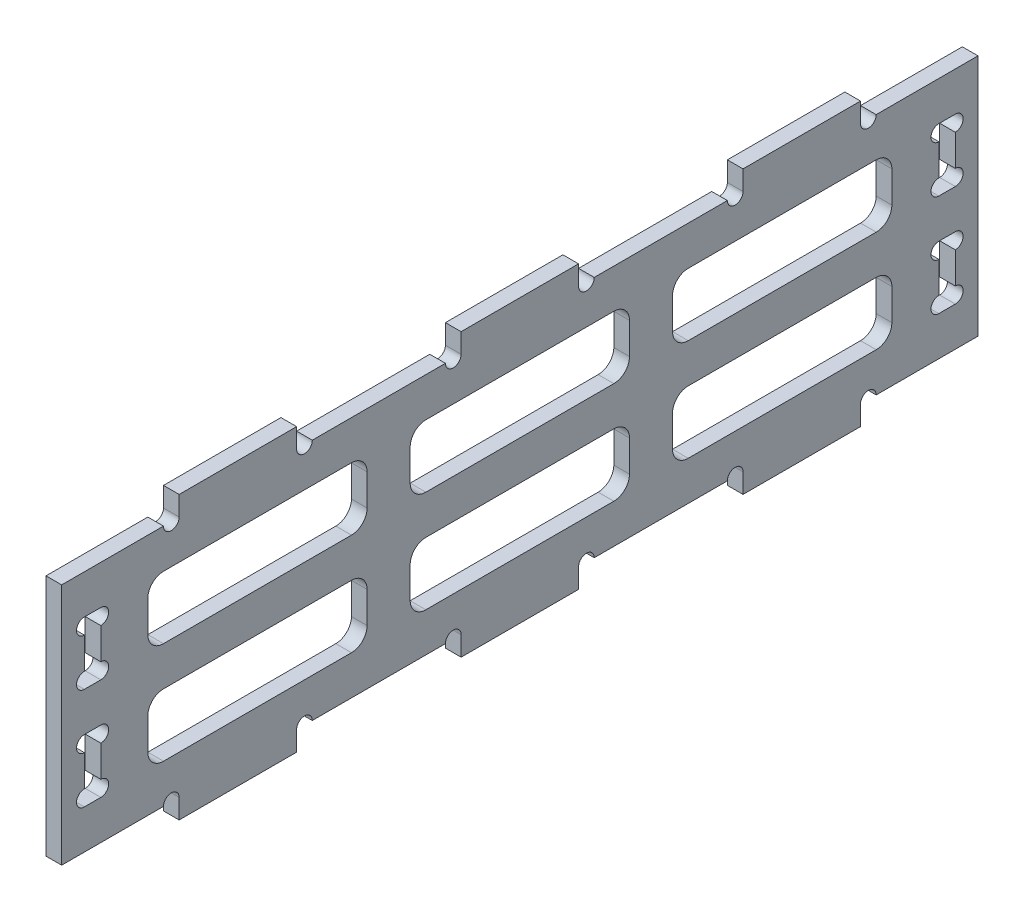
SolidWorks part; units mm, degrees
ref_plane "前视基准面" through (0, 0, 0) normal (0, 0, 1) x (1, 0, 0)
ref_plane "上视基准面" through (0, 0, 0) normal (0, 1, 0) x (1, 0, 0)
ref_plane "右视基准面" through (0, 0, 0) normal (1, 0, 0) x (0, 0, -1)
sketch "草图1" plane through (0, 0, 0) normal (1, 0, 0) x (0, 0, -1)
  line L1 (0, 0) -> (107, 0)
  line L2 (0, 0) -> (0, 31)
  line L3 (0, 31) -> (107, 31)
  line L4 (107, 0) -> (107, 31)
  dimension "D1" = 31
  dimension "D2" = 107
extrude "凸台-拉伸1" add sketch "草图1" along normal blind 2
sketch "草图2" plane through (2, 0, 0) normal (1, 0, 0) x (0, 0, -1)
  line L0 (0, 31) -> (-5, 31)
  line L1 (-5, 31) -> (-5, 0)
  line L2 (-5, 0) -> (0, 0)
  line L4 (0, 31) -> (0, 26)
  line L5 (0, 31) -> (0, 0) construction
  line L6 (0, 26) -> (-2.1, 26)
  line L7 (-2.1, 26) -> (-2.1, 18)
  line L8 (-2.1, 18) -> (0, 18)
  line L9 (0, 18) -> (0, 13)
  line L10 (0, 13) -> (-2.1, 13)
  line L11 (-2.1, 13) -> (-2.1, 5)
  line L12 (-2.1, 5) -> (0, 5)
  line L13 (0, 0) -> (0, 5)
  line L14 (53.5, 31) -> (53.5, 0) construction
  line L15 (107, 31) -> (0, 31) construction
  line L16 (0, 0) -> (107, 0) construction
  line L17 (107, 0) -> (107, 5)
  line L18 (109.1, 5) -> (107, 5)
  line L19 (109.1, 13) -> (109.1, 5)
  line L20 (107, 13) -> (109.1, 13)
  line L21 (107, 18) -> (107, 13)
  line L22 (109.1, 18) -> (107, 18)
  line L23 (109.1, 26) -> (109.1, 18)
  line L24 (107, 26) -> (109.1, 26)
  line L25 (107, 31) -> (107, 26)
  line L26 (112, 0) -> (107, 0)
  line L27 (112, 31) -> (112, 0)
  line L28 (107, 31) -> (112, 31)
  dimension "D1" = 5
  dimension "D2" = 8
  dimension "D3" = 5
  dimension "D4" = 8
  dimension "D5" = 2.1
  dimension "D6" = 5
extrude "凸台-拉伸2" add sketch "草图2" against normal up to surface (2 mm away) up to face at (0, 15.5, -53.5)
sketch "草图3" plane through (2, 0, 0) normal (1, 0, 0) x (0, 0, -1)
  line L0 (-2.1, 24) -> (-2.1, 26)
  line L1 (-2.1, 18) -> (-2.1, 26) construction
  line L2 (-1.05, 26) -> (-1.05, 18) construction
  line L3 (-2.1, 26) -> (0, 26) construction
  line L4 (0, 18) -> (-2.1, 18) construction
  line L5 (-2.1, 22) -> (0, 22) construction
  line L6 (0, 26) -> (0, 18) construction
  line L7 (0, 24) -> (0, 26)
  line L8 (0, 20) -> (0, 18)
  line L9 (-2.1, 20) -> (-2.1, 18)
  line L10 (-1.05, 18) -> (-1.05, 13) construction
  line L11 (-2.1, 13) -> (0, 13) construction
  line L12 (-1.05, 15.5) -> (0, 15.5) construction
  line L13 (-2.1, 9) -> (0, 9) construction
  line L14 (-1.05, 5) -> (-1.05, 13) construction
  line L15 (-2.1, 11) -> (-2.1, 13)
  line L16 (0, 11) -> (0, 13)
  line L17 (0, 7) -> (0, 5)
  line L18 (-2.1, 7) -> (-2.1, 5)
  line L19 (53.5, 31) -> (53.5, 0) construction
  line L20 (112, 31) -> (-5, 31) construction
  line L21 (-5, 0) -> (112, 0) construction
  line L22 (108.05, 5) -> (108.05, 13) construction
  line L23 (109.1, 9) -> (107, 9) construction
  line L24 (108.05, 15.5) -> (107, 15.5) construction
  line L25 (108.05, 18) -> (108.05, 13) construction
  line L26 (109.1, 22) -> (107, 22) construction
  line L27 (108.05, 26) -> (108.05, 18) construction
  line L28 (109.1, 7) -> (109.1, 5)
  line L29 (107, 7) -> (107, 5)
  line L30 (107, 11) -> (107, 13)
  line L31 (109.1, 11) -> (109.1, 13)
  line L32 (109.1, 20) -> (109.1, 18)
  line L33 (107, 20) -> (107, 18)
  line L34 (107, 24) -> (107, 26)
  line L35 (109.1, 24) -> (109.1, 26)
  line L36 (109.1, 26) -> (109.1, 18) construction
  arc A0 (-2.1, 26) -> (-2.1, 24) centre (-2.1, 25) ccw
  arc A1 (0, 26) -> (0, 24) centre (0, 25) cw
  arc A2 (0, 18) -> (0, 20) centre (0, 19) ccw
  arc A3 (-2.1, 18) -> (-2.1, 20) centre (-2.1, 19) cw
  arc A4 (-2.1, 13) -> (-2.1, 11) centre (-2.1, 12) ccw
  arc A5 (0, 13) -> (0, 11) centre (0, 12) cw
  arc A6 (0, 5) -> (0, 7) centre (0, 6) ccw
  arc A7 (-2.1, 5) -> (-2.1, 7) centre (-2.1, 6) cw
  arc A8 (109.1, 5) -> (109.1, 7) centre (109.1, 6) ccw
  arc A9 (107, 5) -> (107, 7) centre (107, 6) cw
  arc A10 (107, 13) -> (107, 11) centre (107, 12) ccw
  arc A11 (109.1, 13) -> (109.1, 11) centre (109.1, 12) cw
  arc A12 (109.1, 18) -> (109.1, 20) centre (109.1, 19) ccw
  arc A13 (107, 18) -> (107, 20) centre (107, 19) cw
  arc A14 (107, 26) -> (107, 24) centre (107, 25) ccw
  arc A15 (109.1, 26) -> (109.1, 24) centre (109.1, 25) cw
  dimension "D1" = 1
extrude "切除-拉伸1" cut sketch "草图3" against normal through all
sketch "草图5" plane through (2, 0, 0) normal (1, 0, 0) x (0, 0, -1)
  line L0 (112, 31) -> (-5, 31) construction
  line L1 (10, 31) -> (25, 31)
  line L2 (10, 31) -> (10, 33.5)
  line L3 (10, 33.5) -> (25, 33.5)
  line L4 (25, 31) -> (25, 33.5)
  line L5 (0, 24) -> (0, 20) construction
  line L6 (46, 31) -> (61, 31)
  line L7 (46, 31) -> (46, 33.5)
  line L8 (46, 33.5) -> (61, 33.5)
  line L9 (61, 31) -> (61, 33.5)
  line L10 (82, 31) -> (97, 31)
  line L11 (82, 31) -> (82, 33.5)
  line L12 (82, 33.5) -> (97, 33.5)
  line L13 (97, 31) -> (97, 33.5)
  line L14 (107, 20) -> (107, 24) construction
  line L15 (-5, 15.5) -> (112, 15.5) construction
  line L16 (-5, 31) -> (-5, 0) construction
  line L17 (112, 0) -> (112, 31) construction
  line L18 (97, 0) -> (97, -2.5)
  line L19 (82, -2.5) -> (97, -2.5)
  line L20 (82, 0) -> (82, -2.5)
  line L21 (82, 0) -> (97, 0)
  line L22 (61, 0) -> (61, -2.5)
  line L23 (46, -2.5) -> (61, -2.5)
  line L24 (46, 0) -> (46, -2.5)
  line L25 (46, 0) -> (61, 0)
  line L26 (25, 0) -> (25, -2.5)
  line L27 (10, -2.5) -> (25, -2.5)
  line L28 (10, 0) -> (10, -2.5)
  line L29 (10, 0) -> (25, 0)
  dimension "D1" = 10
  dimension "D2" = 15
  dimension "D3" = 15
  dimension "D4" = 21
  dimension "D5" = 10
  dimension "D6" = 15
  dimension "D7" = 2.5
extrude "凸台-拉伸3" add sketch "草图5" against normal up to surface (2 mm away) up to face at (0, 9, 1.05)
sketch "草图6" plane through (2, 0, 0) normal (1, 0, 0) x (0, 0, -1)
  line L0 (10, 31) -> (8, 31)
  line L1 (10, 31) -> (-5, 31) construction
  line L2 (17.5, 33.5) -> (17.5, -2.5) construction
  line L3 (25, 33.5) -> (10, 33.5) construction
  line L4 (10, -2.5) -> (25, -2.5) construction
  line L5 (-5, 15.5) -> (112, 15.5) construction
  line L7 (-5, 31) -> (-5, 0) construction
  line L8 (112, 0) -> (112, 31) construction
  line L9 (25, 31) -> (27, 31)
  line L10 (35.5, 31) -> (35.5, 0) construction
  line L11 (46, 31) -> (25, 31) construction
  line L12 (25, 0) -> (46, 0) construction
  line L13 (53.5, 33.5) -> (53.5, -2.5) construction
  line L14 (61, 33.5) -> (46, 33.5) construction
  line L15 (46, -2.5) -> (61, -2.5) construction
  line L16 (46, 31) -> (44, 31)
  line L18 (61, 31) -> (63, 31)
  line L19 (82, 31) -> (80, 31)
  line L20 (97, 31) -> (99, 31)
  line L21 (97, 0) -> (99, 0)
  line L22 (82, 0) -> (80, 0)
  line L23 (61, 0) -> (63, 0)
  line L24 (46, 0) -> (44, 0)
  line L25 (25, 0) -> (27, 0)
  line L26 (10, 0) -> (8, 0)
  arc A0 (10, 31) -> (8, 31) centre (9, 31) cw
  arc A1 (25, 31) -> (27, 31) centre (26, 31) ccw
  arc A2 (46, 31) -> (44, 31) centre (45, 31) cw
  arc A3 (61, 31) -> (63, 31) centre (62, 31) ccw
  arc A4 (82, 31) -> (80, 31) centre (81, 31) cw
  arc A5 (97, 31) -> (99, 31) centre (98, 31) ccw
  arc A6 (97, 0) -> (99, 0) centre (98, 0) cw
  arc A7 (82, 0) -> (80, 0) centre (81, 0) ccw
  arc A8 (61, 0) -> (63, 0) centre (62, 0) cw
  arc A9 (46, 0) -> (44, 0) centre (45, 0) ccw
  arc A10 (25, 0) -> (27, 0) centre (26, 0) cw
  arc A11 (10, 0) -> (8, 0) centre (9, 0) ccw
  dimension "D1" = 1
extrude "切除-拉伸2" cut sketch "草图6" against normal through all
sketch "草图7" plane through (2, 0, 0) normal (1, 0, 0) x (0, 0, -1)
  line L0 (0, 24) -> (0, 20) construction
  line L1 (8, 26) -> (32, 26)
  line L2 (6, 24) -> (6, 20)
  line L3 (8, 18) -> (32, 18)
  line L4 (34, 24) -> (34, 20)
  line L5 (8, 31) -> (-5, 31) construction
  line L6 (39.5, 24) -> (39.5, 20)
  line L7 (41.5, 26) -> (65.5, 26)
  line L8 (67.5, 24) -> (67.5, 20)
  line L9 (41.5, 18) -> (65.5, 18)
  line L10 (73, 24) -> (73, 20)
  line L11 (75, 26) -> (99, 26)
  line L12 (101, 24) -> (101, 20)
  line L13 (75, 18) -> (99, 18)
  line L14 (39.5, 11) -> (39.5, 7)
  line L15 (41.5, 13) -> (65.5, 13)
  line L16 (67.5, 11) -> (67.5, 7)
  line L17 (41.5, 5) -> (65.5, 5)
  line L18 (73, 11) -> (73, 7)
  line L19 (75, 13) -> (99, 13)
  line L20 (101, 11) -> (101, 7)
  line L21 (75, 5) -> (99, 5)
  line L22 (6, 11) -> (6, 7)
  line L23 (8, 13) -> (32, 13)
  line L24 (34, 11) -> (34, 7)
  line L25 (8, 5) -> (32, 5)
  line L26 (-2.1, 13) -> (0, 13) construction
  line L27 (107, 20) -> (107, 24) construction
  arc A0 (32, 18) -> (34, 20) centre (32, 20) ccw
  arc A1 (32, 26) -> (34, 24) centre (32, 24) cw
  arc A2 (6, 20) -> (8, 18) centre (8, 20) ccw
  arc A3 (8, 26) -> (6, 24) centre (8, 24) ccw
  arc A4 (41.5, 26) -> (39.5, 24) centre (41.5, 24) ccw
  arc A5 (39.5, 20) -> (41.5, 18) centre (41.5, 20) ccw
  arc A6 (65.5, 26) -> (67.5, 24) centre (65.5, 24) cw
  arc A7 (65.5, 18) -> (67.5, 20) centre (65.5, 20) ccw
  arc A8 (75, 26) -> (73, 24) centre (75, 24) ccw
  arc A9 (73, 20) -> (75, 18) centre (75, 20) ccw
  arc A10 (99, 26) -> (101, 24) centre (99, 24) cw
  arc A11 (99, 18) -> (101, 20) centre (99, 20) ccw
  arc A12 (41.5, 13) -> (39.5, 11) centre (41.5, 11) ccw
  arc A13 (39.5, 7) -> (41.5, 5) centre (41.5, 7) ccw
  arc A14 (65.5, 13) -> (67.5, 11) centre (65.5, 11) cw
  arc A15 (65.5, 5) -> (67.5, 7) centre (65.5, 7) ccw
  arc A16 (75, 13) -> (73, 11) centre (75, 11) ccw
  arc A17 (73, 7) -> (75, 5) centre (75, 7) ccw
  arc A18 (99, 13) -> (101, 11) centre (99, 11) cw
  arc A19 (99, 5) -> (101, 7) centre (99, 7) ccw
  arc A20 (8, 13) -> (6, 11) centre (8, 11) ccw
  arc A21 (6, 7) -> (8, 5) centre (8, 7) ccw
  arc A22 (32, 13) -> (34, 11) centre (32, 11) cw
  arc A23 (32, 5) -> (34, 7) centre (32, 7) ccw
  point P12 (34, 26)
  point P15 (6, 18)
  point P18 (6, 26)
  point P84 (107, 22)
  dimension "D5" = 2
  dimension "D1" = 28
  dimension "D2" = 6
  dimension "D3" = 5
  dimension "D4" = 8
  dimension "D8" = 6
  dimension "D6" = 3
  dimension "D7" = 2
extrude "切除-拉伸3" cut sketch "草图7" against normal through all
